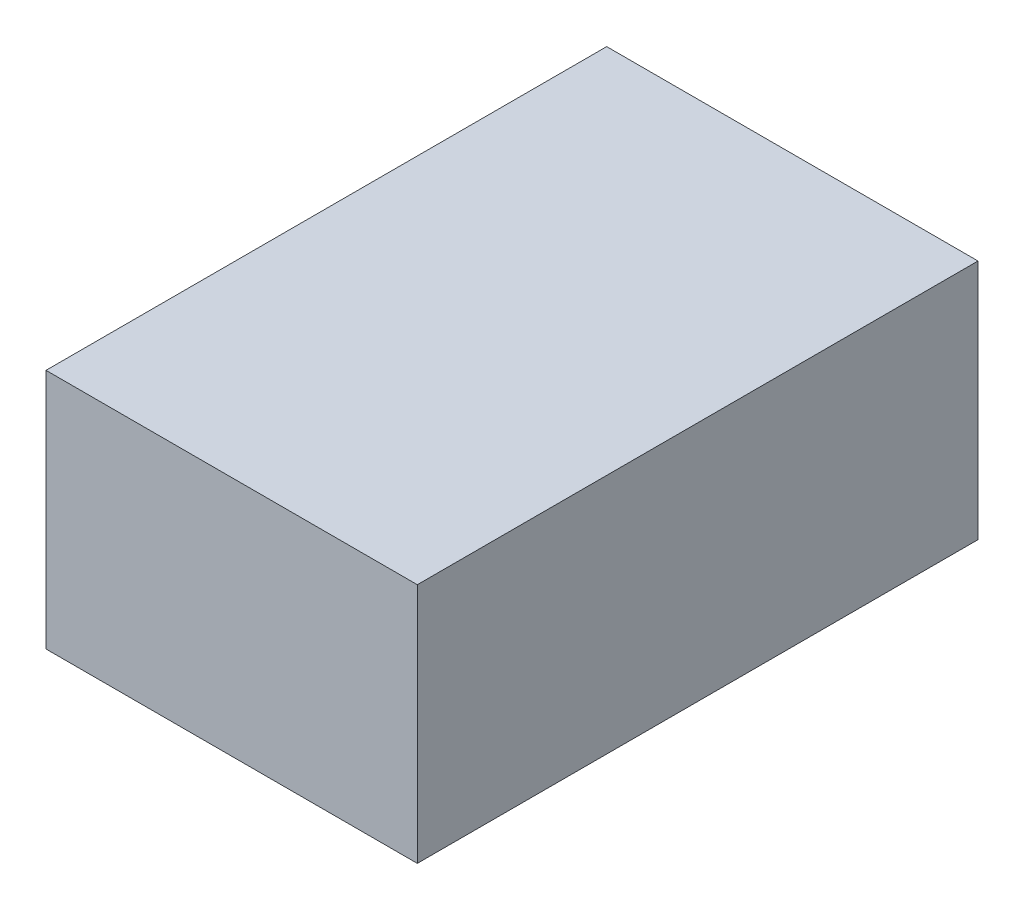
SolidWorks part; units mm, degrees
material "CA"
ref_plane "Front Plane" through (0, 0, 0) normal (0, 0, 1) x (1, 0, 0)
ref_plane "Top Plane" through (0, 0, 0) normal (0, 1, 0) x (1, 0, 0)
ref_plane "Right Plane" through (0, 0, 0) normal (1, 0, 0) x (0, 0, -1)
sketch "Sketch1" plane through (0, 0, 0) normal (0, 0, 1) x (1, 0, 0)
  line L1 (-50, -32.5) -> (50, -32.5)
  line L2 (-50, -32.5) -> (-50, 32.5)
  line L3 (-50, 32.5) -> (50, 32.5)
  line L4 (50, -32.5) -> (50, 32.5)
  line L5 (-50, -32.5) -> (50, 32.5) construction
  line L6 (-50, 32.5) -> (50, -32.5) construction
  point P0 (0, 0)
  dimension "D1" = 100
  dimension "D2" = 65
extrude "Boss-Extrude1" add sketch "Sketch1" along normal blind 151
